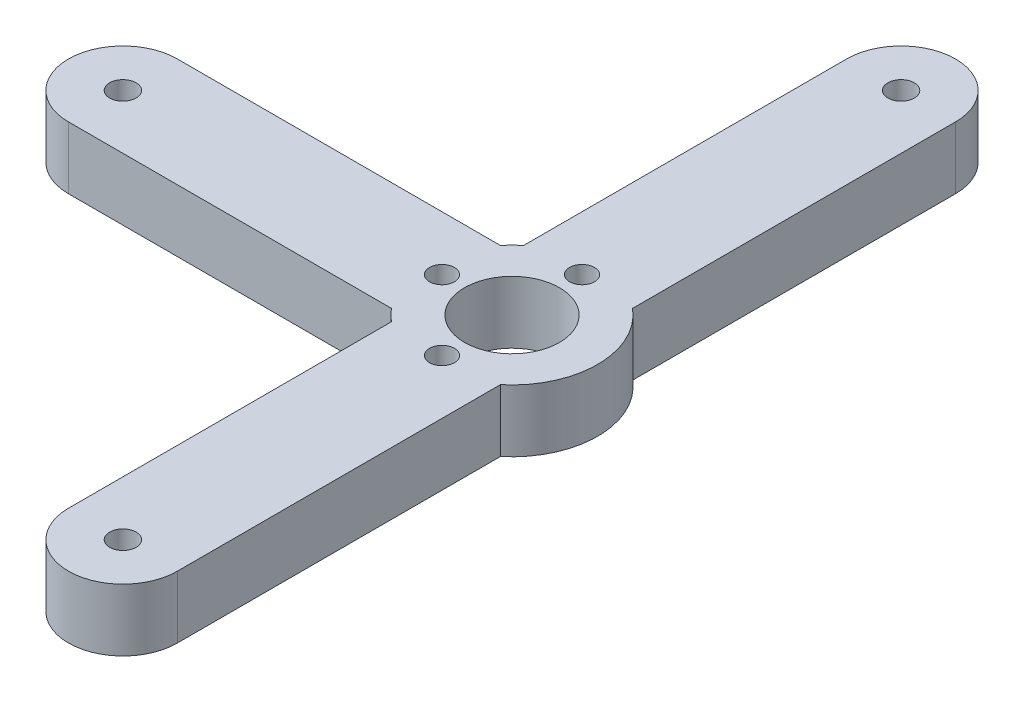
SolidWorks part; units mm, degrees
other "Rear Support Plate Print Blank Left"
ref_plane "Front Plane" through (0, 0, 0) normal (0, 0, 1) x (1, 0, 0)
ref_plane "Top Plane" through (0, 0, 0) normal (0, 1, 0) x (1, 0, 0)
ref_plane "Right Plane" through (0, 0, 0) normal (1, 0, 0) x (0, 0, -1)
sketch3d "Base Outline Sketch datum points"
  point P0 (0, 149, 0)
  point P1 (10, 149, 0)
  point P2 (0, 149, -10)
ref_plane "Base Outline Sketch plane" through (0, 149, 0) normal (0, 1, 0) x (1, 0, 0)
sketch "Base Outline Sketch" plane through (0, 149, 0) normal (0, 1, 0) x (1, 0, 0)
  line L0 (-64.7769, -7) -> (-106.2917, -7)
  line L1 (-63.2917, -50) -> (-63.2917, -8.4853)
  line L2 (-49.2917, -8.4853) -> (-49.2917, -50)
  line L3 (-49.2917, 50) -> (-49.2917, 8.4853)
  line L4 (-63.2917, 8.4853) -> (-63.2917, 50)
  line L5 (-106.2917, 7) -> (-64.7769, 7)
  arc A0 (-63.2917, -8.4853) -> (-64.7769, -7) centre (-56.2917, 0) cw
  arc A1 (-106.2917, -7) -> (-106.2917, 7) centre (-106.2917, 0) cw
  arc A2 (-49.2917, -50) -> (-63.2917, -50) centre (-56.2917, -50) cw
  arc A3 (-49.2917, 8.4853) -> (-49.2917, -8.4853) centre (-56.2917, 0) cw
  arc A4 (-63.2917, 50) -> (-49.2917, 50) centre (-56.2917, 50) cw
  arc A5 (-64.7769, 7) -> (-63.2917, 8.4853) centre (-56.2917, 0) cw
  circle A6 centre (-56.2917, 0) radius 6.1
  circle A7 centre (-106.2917, 0) radius 3.1
  circle A8 centre (-56.2917, 50) radius 3.1
  circle A9 centre (-56.2917, -50) radius 3.1
extrude "Base Outline" add sketch "Base Outline Sketch" along normal blind 1 separate body
sketch3d "Interface Profile 2 Sketch datum points"
  point P0 (0, 150, 0)
  point P1 (10, 150, 0)
  point P2 (0, 150, -10)
ref_plane "Interface Profile 2 Sketch plane" through (0, 150, 0) normal (0, 1, 0) x (1, 0, 0)
sketch "Interface Profile 2 Sketch" plane through (0, 150, 0) normal (0, 1, 0) x (1, 0, 0)
  line L0 (-64.7769, -7) -> (-106.2917, -7)
  line L1 (-63.2917, -50) -> (-63.2917, -8.4853)
  line L2 (-49.2917, -8.4853) -> (-49.2917, -50)
  line L3 (-49.2917, 50) -> (-49.2917, 8.4853)
  line L4 (-63.2917, 8.4853) -> (-63.2917, 50)
  line L5 (-106.2917, 7) -> (-64.7769, 7)
  arc A0 (-63.2917, -8.4853) -> (-64.7769, -7) centre (-56.2917, 0) cw
  arc A1 (-106.2917, -7) -> (-106.2917, 7) centre (-106.2917, 0) cw
  arc A2 (-49.2917, -50) -> (-63.2917, -50) centre (-56.2917, -50) cw
  arc A3 (-49.2917, 8.4853) -> (-49.2917, -8.4853) centre (-56.2917, 0) cw
  arc A4 (-63.2917, 50) -> (-49.2917, 50) centre (-56.2917, 50) cw
  arc A5 (-64.7769, 7) -> (-63.2917, 8.4853) centre (-56.2917, 0) cw
  circle A6 centre (-56.2917, 0) radius 6.1
  circle A7 centre (-106.2917, 0) radius 3.1
  circle A8 centre (-56.2917, 50) radius 3.1
  circle A9 centre (-56.2917, -50) radius 3.1
  circle A10 centre (-65.2917, 0) radius 1.1
  circle A11 centre (-56.2917, -9) radius 1.1
  circle A12 centre (-56.2917, 9) radius 1.1
extrude "Interface Profile 2" add sketch "Interface Profile 2 Sketch" along normal blind 0.6
sketch3d "Interface Profile 3 Sketch datum points"
  point P0 (0, 150.6, 0)
  point P1 (10, 150.6, 0)
  point P2 (0, 150.6, -10)
ref_plane "Interface Profile 3 Sketch plane" through (0, 150.6, 0) normal (0, 1, 0) x (1, 0, 0)
sketch "Interface Profile 3 Sketch" plane through (0, 150.6, 0) normal (0, 1, 0) x (1, 0, 0)
  line L0 (-64.7769, -7) -> (-106.2917, -7)
  line L1 (-63.2917, -50) -> (-63.2917, -8.4853)
  line L2 (-49.2917, -8.4853) -> (-49.2917, -50)
  line L3 (-49.2917, 50) -> (-49.2917, 8.4853)
  line L4 (-63.2917, 8.4853) -> (-63.2917, 50)
  line L5 (-106.2917, 7) -> (-64.7769, 7)
  arc A0 (-63.2917, -8.4853) -> (-64.7769, -7) centre (-56.2917, 0) cw
  arc A1 (-106.2917, -7) -> (-106.2917, 7) centre (-106.2917, 0) cw
  arc A2 (-49.2917, -50) -> (-63.2917, -50) centre (-56.2917, -50) cw
  arc A3 (-49.2917, 8.4853) -> (-49.2917, -8.4853) centre (-56.2917, 0) cw
  arc A4 (-63.2917, 50) -> (-49.2917, 50) centre (-56.2917, 50) cw
  arc A5 (-64.7769, 7) -> (-63.2917, 8.4853) centre (-56.2917, 0) cw
  circle A6 centre (-106.2917, 0) radius 1.7
  circle A7 centre (-56.2917, 50) radius 1.7
  circle A8 centre (-56.2917, 0) radius 6.1
  circle A9 centre (-56.2917, -50) radius 1.7
  circle A10 centre (-65.2917, 0) radius 1.1
  circle A11 centre (-56.2917, -9) radius 1.1
  circle A12 centre (-56.2917, 9) radius 1.1
extrude "Interface Profile 3" add sketch "Interface Profile 3 Sketch" along normal blind 2.4
sketch3d "Interface Profile 4 Sketch datum points"
  point P0 (0, 153, 0)
  point P1 (10, 153, 0)
  point P2 (0, 153, -10)
ref_plane "Interface Profile 4 Sketch plane" through (0, 153, 0) normal (0, 1, 0) x (1, 0, 0)
sketch "Interface Profile 4 Sketch" plane through (0, 153, 0) normal (0, 1, 0) x (1, 0, 0)
  line L0 (-64.7769, -7) -> (-106.2917, -7)
  line L1 (-63.2917, -50) -> (-63.2917, -8.4853)
  line L2 (-49.2917, -8.4853) -> (-49.2917, -50)
  line L3 (-49.2917, 50) -> (-49.2917, 8.4853)
  line L4 (-63.2917, 8.4853) -> (-63.2917, 50)
  line L5 (-106.2917, 7) -> (-64.7769, 7)
  arc A0 (-63.2917, -8.4853) -> (-64.7769, -7) centre (-56.2917, 0) cw
  arc A1 (-106.2917, -7) -> (-106.2917, 7) centre (-106.2917, 0) cw
  arc A2 (-49.2917, -50) -> (-63.2917, -50) centre (-56.2917, -50) cw
  arc A3 (-49.2917, 8.4853) -> (-49.2917, -8.4853) centre (-56.2917, 0) cw
  arc A4 (-63.2917, 50) -> (-49.2917, 50) centre (-56.2917, 50) cw
  arc A5 (-64.7769, 7) -> (-63.2917, 8.4853) centre (-56.2917, 0) cw
  circle A6 centre (-106.2917, 0) radius 1.7
  circle A7 centre (-56.2917, 50) radius 1.7
  circle A8 centre (-56.2917, 0) radius 6.1
  circle A9 centre (-56.2917, -50) radius 1.7
  circle A10 centre (-65.2917, 0) radius 1.6
  circle A11 centre (-56.2917, -9) radius 1.6
  circle A12 centre (-56.2917, 9) radius 1.6
extrude "Interface Profile 4" add sketch "Interface Profile 4 Sketch" along normal blind 4
